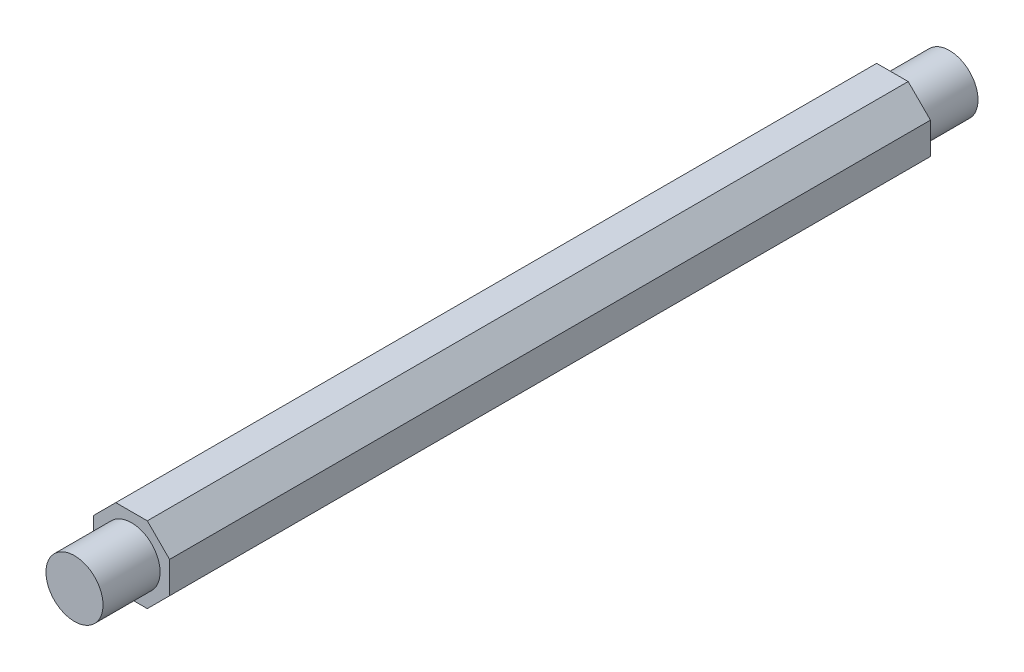
SolidWorks part; units mm, degrees
ref_plane "Alzado" through (0, 0, 0) normal (0, 0, 1) x (1, 0, 0)
ref_plane "Planta" through (0, 0, 0) normal (0, 1, 0) x (1, 0, 0)
ref_plane "Vista lateral" through (0, 0, 0) normal (1, 0, 0) x (0, 0, -1)
sketch "Croquis1" plane through (0, 0, 0) normal (0, 0, 1) x (1, 0, 0)
  circle A0 centre (0, 0) radius 1.5
  dimension "D1" = 3
extrude "Saliente-Extruir1" add sketch "Croquis1" along normal blind 46
sketch "Croquis2" plane through (0, 0, 46) normal (0, 0, 1) x (1, 0, 0)
  line L0 (0, 0) -> (0, -1.7114) construction
  line L1 (0, 0) -> (2, 0) construction
  line L2 (-0.8284, -2) -> (0.8284, -2)
  line L3 (0, 0) -> (-1.6893, 1.6893) construction
  line L4 (-2, 0.8284) -> (-2, -0.8284)
  line L5 (-2, -0.8284) -> (-0.8284, -2)
  line L6 (-2, 0.8284) -> (-0.8284, 2)
  line L7 (-0.8284, 2) -> (0.8284, 2)
  line L8 (0.8284, 2) -> (2, 0.8284)
  line L9 (2, 0.8284) -> (2, -0.8284)
  line L10 (2, -0.8284) -> (0.8284, -2)
  circle A1 centre (0, 0) radius 1.5 construction
  dimension "D1" = 135
  dimension "D2" = 1.6569
  dimension "D3" = 0.5
  dimension "D4" = 0.5
  dimension "D5" = 0.5
  dimension "D6" = 4
  dimension "D7" = 4
  dimension "D8" = 4
extrude "Saliente-Extruir2" add sketch "Croquis2" against normal blind 43
sketch "Croquis3" plane through (0, 0, 46) normal (0, 0, 1) x (1, 0, 0)
  circle A0 centre (0, 0) radius 3.1538
  circle A1 centre (0, 0) radius 1.5
  dimension "D1" = 3
extrude "Cortar-Extruir1" cut sketch "Croquis3" against normal blind 3
